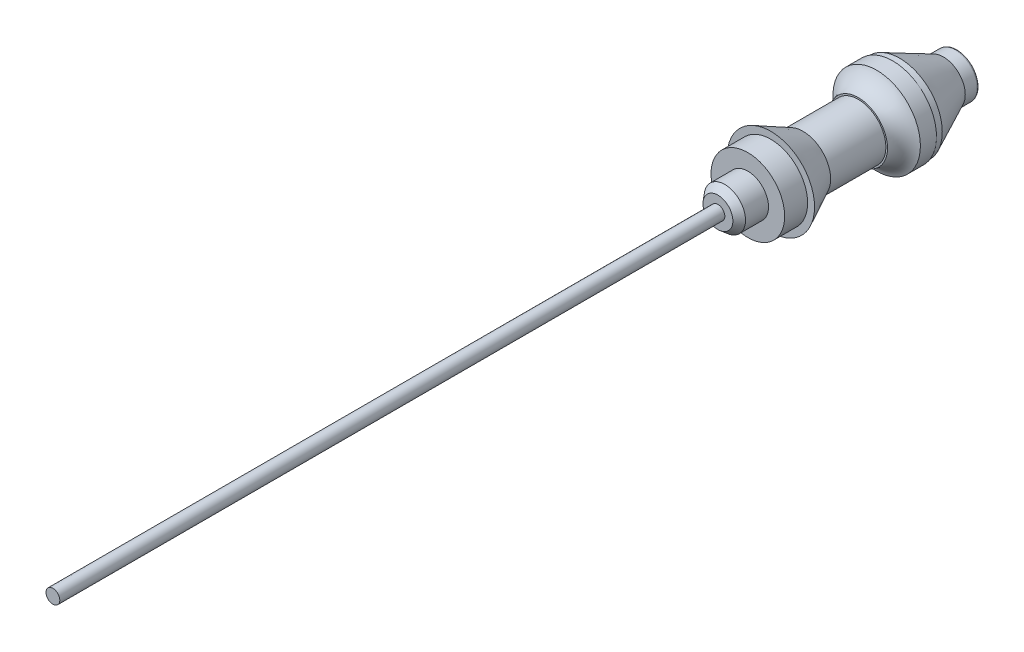
SolidWorks part; units mm, degrees
ref_plane "Спереди" through (0, 0, 0) normal (0, 0, 1) x (1, 0, 0)
ref_plane "Сверху" through (0, 0, 0) normal (0, 1, 0) x (1, 0, 0)
ref_plane "Справа" through (0, 0, 0) normal (1, 0, 0) x (0, 0, -1)
sketch "Эскиз1" plane through (0, 0, 0) normal (1, 0, 0) x (0, 0, -1)
  line L0 (0, 0) -> (635.9472, 0) construction
  line L1 (0, 0) -> (0, 3)
  line L2 (0, 3) -> (289, 3)
  line L3 (289, 3) -> (289, 6.5)
  line L4 (289, 6.5) -> (291.9991, 9)
  line L5 (291.9991, 9) -> (301.9991, 9)
  line L6 (301.9991, 9) -> (301.9991, 16)
  line L7 (301.9991, 16) -> (311.9991, 16)
  line L8 (311.9991, 16) -> (311.9991, 19)
  line L9 (311.9991, 19) -> (325.9991, 12)
  line L10 (325.9991, 12) -> (349.9991, 12)
  line L11 (349.9991, 12) -> (349.9991, 12.7)
  line L12 (357.9991, 19) -> (365, 19)
  line L13 (365, 19) -> (365, 18.5)
  line L14 (365, 18.5) -> (368, 18.5)
  line L15 (368, 18.5) -> (387, 9.5)
  line L16 (387, 9.5) -> (392.2, 9.5)
  line L17 (393, 8.7) -> (393, 0)
  line L20 (393, 0) -> (0, 0)
  arc A0 (349.9991, 12.7) -> (357.9991, 19) centre (348.6741, 22.6118) ccw
  arc A1 (392.2, 9.5) -> (393, 8.7) centre (392.2, 8.7) cw
  point P26 (393, 9.5)
  dimension "D13" = 20
  dimension "D21" = 0.8
  dimension "D1" = 3
  dimension "D2" = 289
  dimension "D3" = 6.5
  dimension "D4" = 2.9991
  dimension "D5" = 9
  dimension "D6" = 10
  dimension "D7" = 16
  dimension "D8" = 19
  dimension "D9" = 10
  dimension "D10" = 14
  dimension "D11" = 12
  dimension "D12" = 24
  dimension "D14" = 19
  dimension "D15" = 104
  dimension "D16" = 6
  dimension "D17" = 3
  dimension "D18" = 19
  dimension "D19" = 18.5
  dimension "D20" = 9.5
  dimension "D22" = 12.7
  dimension "D23" = 8
revolve "Повернуть1" add sketch "Эскиз1" angle 360 about L0
